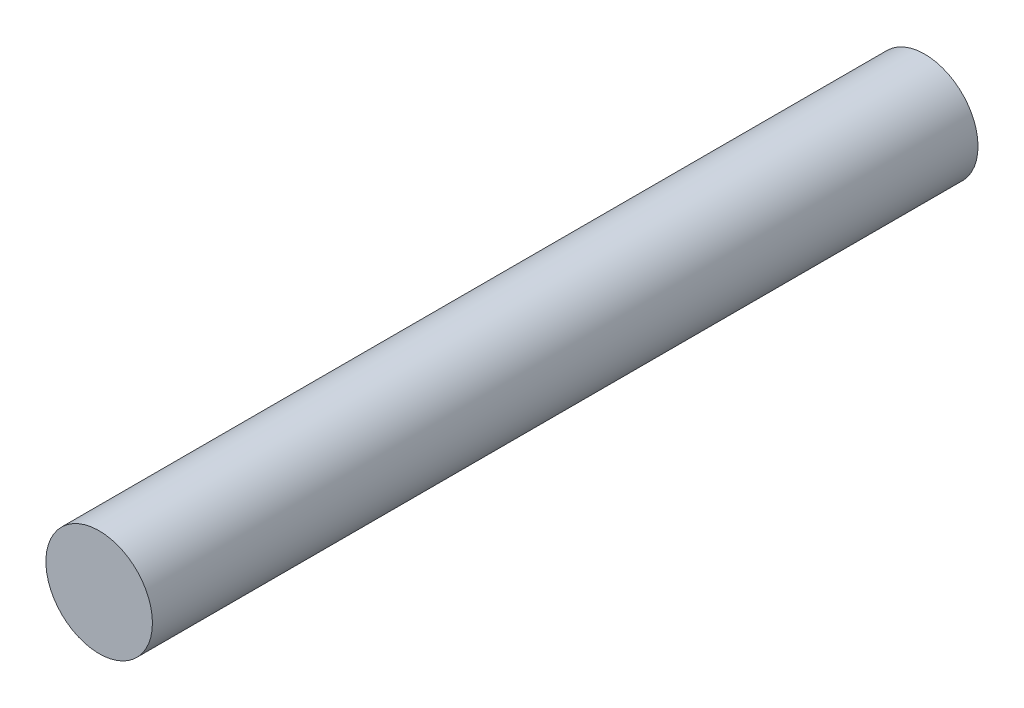
SolidWorks part; units mm, degrees
ref_plane "Front Plane" through (0, 0, 0) normal (0, 0, 1) x (1, 0, 0)
ref_plane "Top Plane" through (0, 0, 0) normal (0, 1, 0) x (1, 0, 0)
ref_plane "Right Plane" through (0, 0, 0) normal (1, 0, 0) x (0, 0, -1)
sketch "Sketch1" plane through (0, 0, 0) normal (0, 0, 1) x (1, 0, 0)
  circle A0 centre (0, 0) radius 3.175
  dimension "D1" = 6.35
extrude "Boss-Extrude1" add sketch "Sketch1" along normal blind 49.2125
